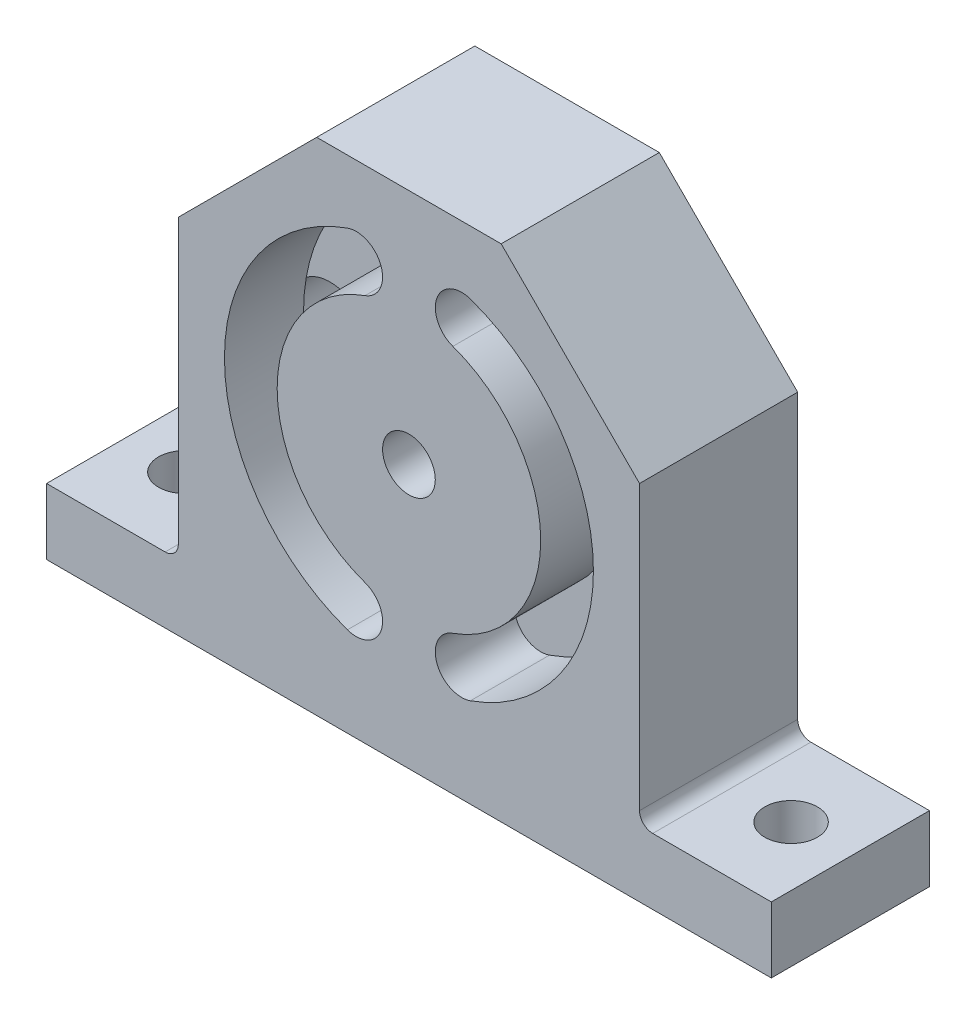
SolidWorks part; units mm, degrees
ref_plane "Front Plane" through (0, 0, 0) normal (0, 0, 1) x (1, 0, 0)
ref_plane "Top Plane" through (0, 0, 0) normal (0, 1, 0) x (1, 0, 0)
ref_plane "Right Plane" through (0, 0, 0) normal (1, 0, 0) x (0, 0, -1)
sketch "Sketch1" plane through (0, 0, 0) normal (0, 0, 1) x (1, 0, 0)
  line L0 (0, 0) -> (55, 0)
  line L1 (55, 0) -> (55, 5)
  line L2 (55, 5) -> (45, 5)
  line L3 (45, 5) -> (45, 27.5)
  line L4 (45, 27.5) -> (34.5, 38)
  line L5 (34.5, 38) -> (20.5, 38)
  line L6 (20.5, 38) -> (10, 27.5)
  line L7 (10, 27.5) -> (10, 5)
  line L8 (10, 5) -> (0, 5)
  line L9 (0, 5) -> (0, 0)
  line L10 (27.5, 38) -> (27.5, -15.5098) construction
  point P13 (0, 0)
  dimension "D1" = 7
  dimension "D2" = 27.5
  dimension "D3" = 5
  dimension "D4" = 5
  dimension "D5" = 22.5
  dimension "D6" = 22.5
  dimension "D7" = 10.5
extrude "Boss-Extrude1" add sketch "Sketch1" along normal mid plane 12
sketch "Sketch2" plane through (0, 0, 6) normal (0, 0, 1) x (1, 0, 0)
  line L0 (27.5, 38) -> (27.5, -4.1201) construction
  line L1 (34.5, 38) -> (20.5, 38) construction
  line L2 (0, 0) -> (55, 0) construction
  circle A0 centre (27.5, 20) radius 2
  point P6 (0, 0)
  dimension "D1" = 4
  dimension "D2" = 20
extrude "Cut-Extrude1" cut sketch "Sketch2" against normal through all
sketch "Sketch3" plane through (0, 0, 6) normal (0, 0, 1) x (1, 0, 0)
  line L0 (27.5, 38) -> (27.5, -3.849) construction
  line L1 (34.5, 38) -> (20.5, 38) construction
  arc A0 (24.1667, 29.4281) -> (24.1667, 10.5719) centre (27.5, 20) ccw
  arc A1 (22.8333, 33.1993) -> (22.8333, 6.8007) centre (27.5, 20) ccw
  arc A2 (24.1667, 29.4281) -> (22.8333, 33.1993) centre (23.5, 31.3137) ccw
  arc A3 (22.8333, 6.8007) -> (24.1667, 10.5719) centre (23.5, 8.6863) ccw
  arc A4 (32.1667, 6.8007) -> (30.8333, 10.5719) centre (31.5, 8.6863) cw
  arc A5 (30.8333, 29.4281) -> (32.1667, 33.1993) centre (31.5, 31.3137) cw
  arc A6 (30.8333, 10.5719) -> (30.8333, 29.4281) centre (27.5, 20) ccw
  arc A7 (32.1667, 6.8007) -> (32.1667, 33.1993) centre (27.5, 20) ccw
  point P13 (0, 0)
  dimension "D1" = 20
  dimension "D3" = 4
  dimension "D4" = 4
extrude "Cut-Extrude2" cut sketch "Sketch3" against normal blind 6
sketch "Sketch4" plane through (0, 0, -6) normal (0, 0, -1) x (-1, 0, 0)
  circle A0 centre (-39.5, 20) radius 3
  circle A1 centre (-15.5, 20) radius 3
  point P0 (-27.5, 20)
  point P6 (0, 0)
  point P7 (0, 0)
  point P8 (0, 0)
  point P10 (0, 0)
  point P11 (0, 0)
  dimension "D3" = 6
  dimension "D1" = 12
  dimension "D2" = 12
extrude "Cut-Extrude3" cut sketch "Sketch4" against normal blind 6
sketch "Sketch5" plane through (0, 5, 0) normal (0, 1, 0) x (1, 0, 0)
  line L0 (27.5, 6) -> (27.5, -7.0742) construction
  line L1 (34.5, 6) -> (20.5, 6) construction
  circle A0 centre (4.5, 0) radius 2
  circle A1 centre (50.5, 0) radius 2
  dimension "D1" = 4
  dimension "D2" = 23
  dimension "D3" = 23
extrude "Cut-Extrude4" cut sketch "Sketch5" against normal through all
fillet "Fillet1" radius 1 2 edges at (10, 5, 0) (45, 5, 0)
